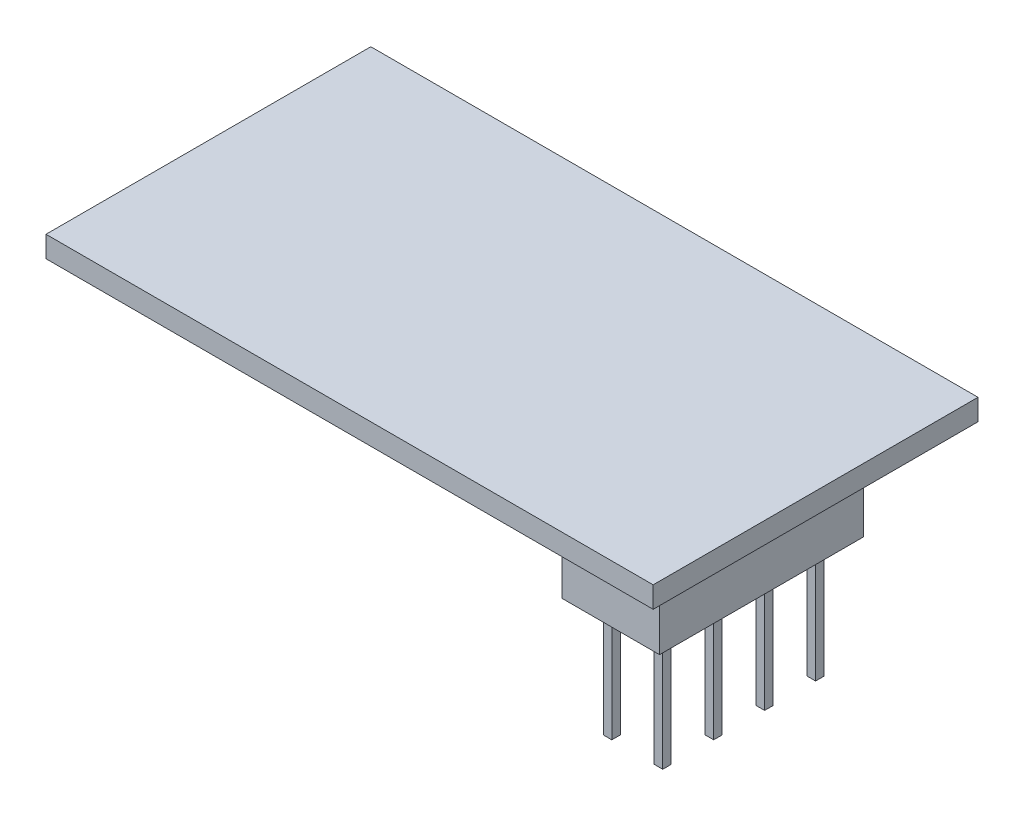
SolidWorks part; units mm, degrees
ref_plane "前视基准面" through (0, 0, 0) normal (0, 0, 1) x (1, 0, 0)
ref_plane "上视基准面" through (0, 0, 0) normal (0, 1, 0) x (1, 0, 0)
ref_plane "右视基准面" through (0, 0, 0) normal (1, 0, 0) x (0, 0, -1)
other "Configuration Table"
sketch "草图1" plane through (0, 0, 0) normal (0, 1, 0) x (1, 0, 0)
  line L1 (-14.3, 7.65) -> (14.3, 7.65)
  line L2 (-14.3, 7.65) -> (-14.3, -7.65)
  line L3 (-14.3, -7.65) -> (14.3, -7.65)
  line L4 (14.3, 7.65) -> (14.3, -7.65)
  line L5 (-14.3, 7.65) -> (14.3, -7.65) construction
  line L6 (-14.3, -7.65) -> (14.3, 7.65) construction
  point P0 (0, 0)
  dimension "D1" = 28.6
  dimension "D2" = 15.3
extrude "凸台-拉伸1" add sketch "草图1" along normal blind 1
sketch "草图2" plane through (0, 0, 0) normal (0, -1, 0) x (1, 0, 0)
  line L0 (-14.3, 7.65) -> (14.3, 7.65) construction
  line L1 (9.2, 6.85) -> (13.8, 6.85)
  line L2 (9.2, 6.85) -> (9.2, -2.75)
  line L3 (9.2, -2.75) -> (13.8, -2.75)
  line L4 (13.8, 6.85) -> (13.8, -2.75)
  line L5 (14.3, 7.65) -> (14.3, -7.65) construction
  dimension "D1" = 9.6
  dimension "D2" = 4.6
  dimension "D3" = 0.8
  dimension "D4" = 0.5
extrude "凸台-拉伸2" add sketch "草图2" along normal blind 2.5
sketch "草图3" plane through (0, -2.5, 0) normal (0, -1, 0) x (1, 0, 0)
  line L0 (11.5, 6.85) -> (11.5, -2.75) construction
  line L1 (13.8, 6.85) -> (9.2, 6.85) construction
  line L2 (9.2, -2.75) -> (13.8, -2.75) construction
  line L3 (11.5, -2.75) -> (11.5, 2.05) construction
  line L4 (11.5, 2.05) -> (9.2, 2.05) construction
  line L5 (9.2, 6.85) -> (9.2, -2.75) construction
  line L6 (9.2, 2.05) -> (9.2, 6.85) construction
  line L7 (9.2, 6.85) -> (11.5, 6.85) construction
  line L8 (11.5, 6.85) -> (11.5, 4.45) construction
  line L9 (11.5, 4.45) -> (9.2, 4.45) construction
  line L10 (10.35, 6.85) -> (10.35, 4.45) construction
  line L11 (10.35, 4.45) -> (11.5, 5.65) construction
  line L12 (11.5, 5.65) -> (10.35, 5.65) construction
  line L13 (12.55, 5.85) -> (12.95, 5.85)
  line L14 (10.15, 5.85) -> (10.55, 5.85)
  line L15 (10.15, 5.85) -> (10.15, 5.45)
  line L16 (10.15, 5.45) -> (10.55, 5.45)
  line L17 (10.55, 5.85) -> (10.55, 5.45)
  line L18 (10.15, 5.85) -> (10.55, 5.45) construction
  line L19 (10.15, 5.45) -> (10.55, 5.85) construction
  line L20 (12.55, 5.85) -> (12.55, 5.45)
  line L21 (12.55, 5.45) -> (12.95, 5.45)
  line L22 (12.95, 5.85) -> (12.95, 5.45)
  line L23 (12.55, 5.85) -> (12.95, 5.45) construction
  line L24 (12.55, 5.45) -> (12.95, 5.85) construction
  line L25 (12.55, 3.45) -> (12.95, 3.45)
  line L26 (12.55, 3.45) -> (12.55, 3.05)
  line L27 (12.55, 3.05) -> (12.95, 3.05)
  line L28 (12.95, 3.45) -> (12.95, 3.05)
  line L29 (12.55, 3.45) -> (12.95, 3.05) construction
  line L30 (12.55, 3.05) -> (12.95, 3.45) construction
  line L31 (12.55, 1.05) -> (12.95, 1.05)
  line L32 (12.55, 1.05) -> (12.55, 0.65)
  line L33 (12.55, 0.65) -> (12.95, 0.65)
  line L34 (12.95, 1.05) -> (12.95, 0.65)
  line L35 (12.55, 1.05) -> (12.95, 0.65) construction
  line L36 (12.55, 0.65) -> (12.95, 1.05) construction
  line L37 (12.55, -1.35) -> (12.95, -1.35)
  line L38 (12.55, -1.35) -> (12.55, -1.75)
  line L39 (12.55, -1.75) -> (12.95, -1.75)
  line L40 (12.95, -1.35) -> (12.95, -1.75)
  line L41 (12.55, -1.35) -> (12.95, -1.75) construction
  line L42 (12.55, -1.75) -> (12.95, -1.35) construction
  line L43 (10.15, 3.45) -> (10.55, 3.45)
  line L44 (10.15, 3.45) -> (10.15, 3.05)
  line L45 (10.15, 3.05) -> (10.55, 3.05)
  line L46 (10.55, 3.45) -> (10.55, 3.05)
  line L47 (10.15, 3.45) -> (10.55, 3.05) construction
  line L48 (10.15, 3.05) -> (10.55, 3.45) construction
  line L49 (10.15, 1.05) -> (10.55, 1.05)
  line L50 (10.15, 1.05) -> (10.15, 0.65)
  line L51 (10.15, 0.65) -> (10.55, 0.65)
  line L52 (10.55, 1.05) -> (10.55, 0.65)
  line L53 (10.15, 1.05) -> (10.55, 0.65) construction
  line L54 (10.15, 0.65) -> (10.55, 1.05) construction
  line L55 (10.15, -1.35) -> (10.55, -1.35)
  line L56 (10.15, -1.35) -> (10.15, -1.75)
  line L57 (10.15, -1.75) -> (10.55, -1.75)
  line L58 (10.55, -1.35) -> (10.55, -1.75)
  line L59 (10.15, -1.35) -> (10.55, -1.75) construction
  line L60 (10.15, -1.75) -> (10.55, -1.35) construction
  dimension "D1" = 0.4
  dimension "D2" = 0.4
  dimension "D3" = 2
  dimension "D4" = 4
extrude "凸台-拉伸3" add sketch "草图3" along normal blind 5.6
